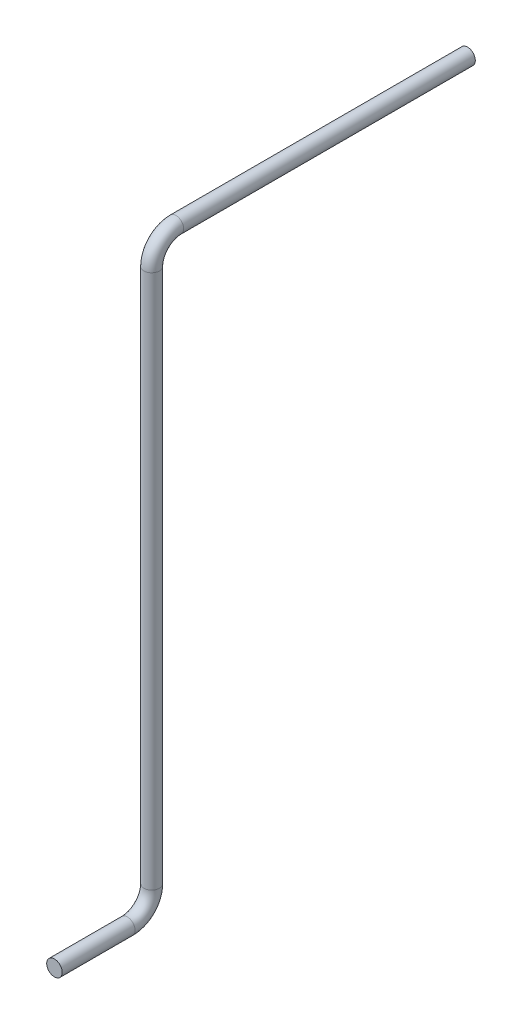
SolidWorks part; units mm, degrees
ref_plane "Front Plane" through (0, 0, 0) normal (0, 0, 1) x (1, 0, 0)
ref_plane "Top Plane" through (0, 0, 0) normal (0, 1, 0) x (1, 0, 0)
ref_plane "Right Plane" through (0, 0, 0) normal (1, 0, 0) x (0, 0, -1)
sketch "Sketch1" plane through (0, 0, 0) normal (0, 0, 1) x (1, 0, 0)
  circle A0 centre (0, 0) radius 1.6
  dimension "D1" = 3.2
sketch "Sketch2" plane through (0, 0, 0) normal (1, 0, 0) x (0, 0, -1)
  line L0 (0, 0) -> (15, 0)
  line L1 (20, 5) -> (20, 115)
  line L2 (25, 120) -> (85, 120)
  arc A0 (15, 0) -> (20, 5) centre (15, 5) ccw
  arc A1 (20, 115) -> (25, 120) centre (25, 115) cw
  dimension "D4" = 5
  dimension "D5" = 5
  dimension "D1" = 20
  dimension "D2" = 120
  dimension "D3" = 60
sweep "Sweep1" add profiles "Sketch1" path "Sketch2"
